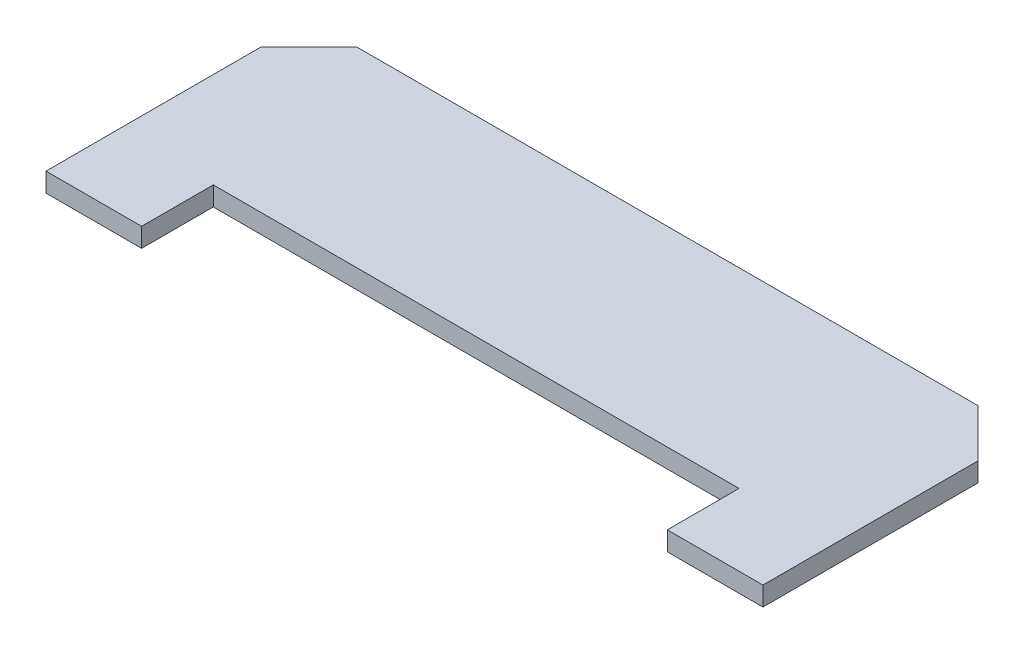
SolidWorks part; units mm, degrees
material "PET"
ref_plane "Front Plane" through (0, 0, 0) normal (0, 0, 1) x (1, 0, 0)
ref_plane "Top Plane" through (0, 0, 0) normal (0, 1, 0) x (1, 0, 0)
ref_plane "Right Plane" through (0, 0, 0) normal (1, 0, 0) x (0, 0, -1)
sketch "Sketch1" plane through (0, 0, 0) normal (0, 1, 0) x (1, 0, 0)
  line L0 (3.4169, -10) -> (13.4169, 0)
  line L1 (13.4169, 0) -> (143.4169, 0)
  line L2 (143.4169, 0) -> (153.4169, -10)
  line L3 (153.4169, -10) -> (153.4169, -55)
  line L4 (153.4169, -55) -> (133.4169, -55)
  line L5 (133.4169, -55) -> (133.4169, -40)
  line L6 (133.4169, -40) -> (23.4169, -40)
  line L7 (23.4169, -40) -> (23.4169, -55)
  line L8 (23.4169, -55) -> (3.4169, -55)
  line L9 (3.4169, -55) -> (3.4169, -10)
  dimension "D1" = 20
  dimension "D2" = 110
  dimension "D3" = 15
  dimension "D4" = 55
  dimension "D5" = 10
  dimension "D6" = 10
  dimension "D7" = 150
extrude "body" add sketch "Sketch1" along normal blind 4
sketch "Sketch2" plane through (0, 4, 0) normal (0, 1, 0) x (1, 0, 0)
  line L0 (80.1705, -15.9424) -> (17.6797, -47.5066)
  line L1 (17.6797, -47.5066) -> (142.6613, -47.5066)
  line L2 (142.6613, -47.5066) -> (80.1705, -15.9424)
